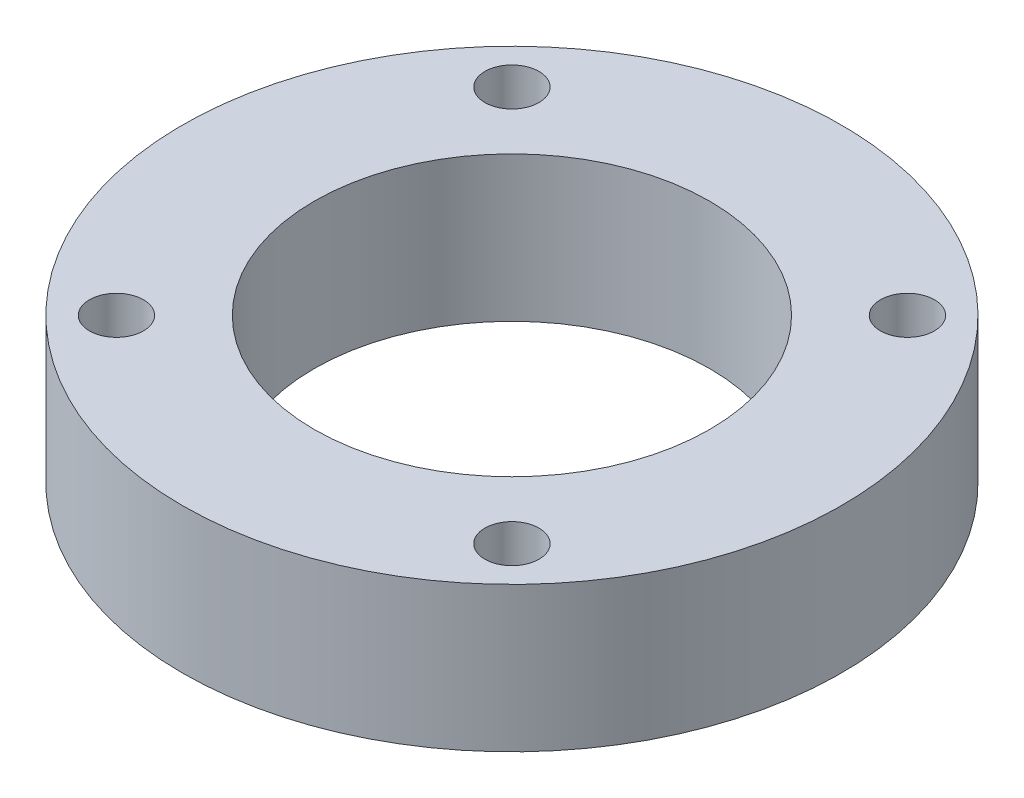
SolidWorks part; units mm, degrees
material "1060 合金"
ref_plane "前视基准面" through (0, 0, 0) normal (0, 0, 1) x (1, 0, 0)
ref_plane "上视基准面" through (0, 0, 0) normal (0, 1, 0) x (1, 0, 0)
ref_plane "右视基准面" through (0, 0, 0) normal (1, 0, 0) x (0, 0, -1)
sketch "草图1" plane through (0, 0, 0) normal (0, 1, 0) x (1, 0, 0)
  line L1 (-15, -15) -> (15, -15) construction
  line L2 (-15, -15) -> (-15, 15) construction
  line L3 (-15, 15) -> (15, 15) construction
  line L4 (15, -15) -> (15, 15) construction
  circle A0 centre (0, 0) radius 25
  circle A1 centre (-15, 15) radius 2.05
  circle A2 centre (15, 15) radius 2.05
  circle A3 centre (15, -15) radius 2.05
  circle A4 centre (-15, -15) radius 2.05
  dimension "D3" = 15
  dimension "D4" = 50
  dimension "D5" = 4.1
  dimension "D1" = 30
  dimension "D2" = 15
extrude "凸台-拉伸1" add sketch "草图1" along normal blind 11
sketch "草图2" plane through (0, 11, 0) normal (0, 1, 0) x (1, 0, 0)
  circle A0 centre (0, 0) radius 15
  dimension "D1" = 30
extrude "切除-拉伸1" cut sketch "草图2" against normal through all
